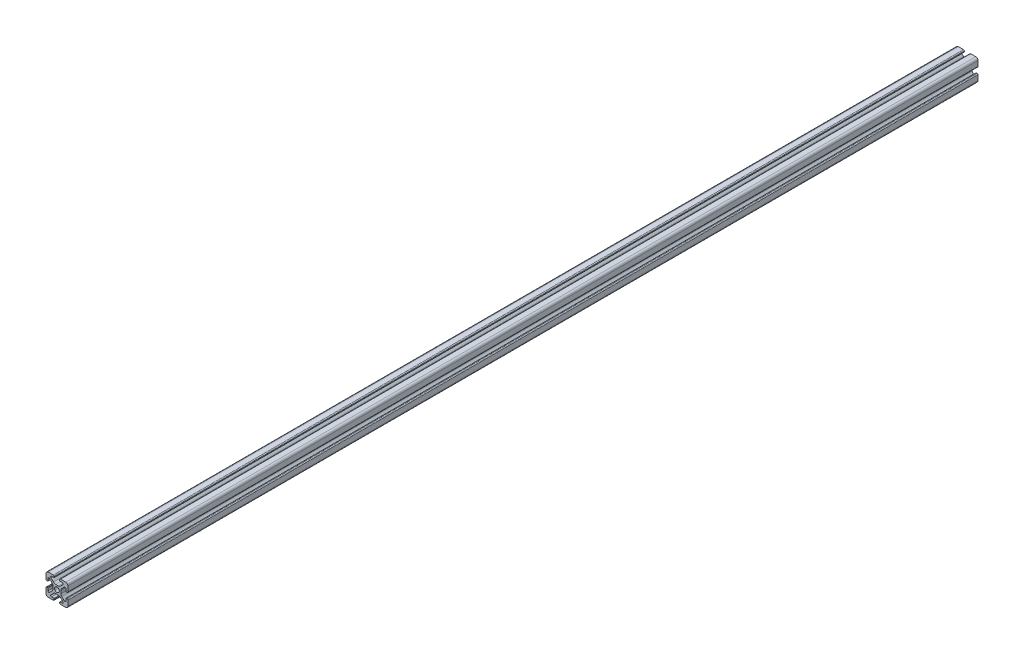
SolidWorks part; units mm, degrees
ref_plane "Plan de face" through (0, 0, 0) normal (0, 0, 1) x (1, 0, 0)
ref_plane "Plan de dessus" through (0, 0, 0) normal (0, 1, 0) x (1, 0, 0)
ref_plane "Plan de droite" through (0, 0, 0) normal (1, 0, 0) x (0, 0, -1)
ref_plane "Plan1" through (0, 0, 0) normal (0, 0, -1) x (-1, 0, 0)
sketch "Esquisse1" plane through (0, 0, 0) normal (0, 0, -1) x (-1, 0, 0)
  line L0 (-20, 6.7) -> (-20, 2)
  line L1 (-18, 0) -> (-13.3, 0)
  line L2 (-12.5, 0.8) -> (-12.5, 1.5)
  line L3 (-12.8, 1.8) -> (-14.9184, 1.8)
  line L4 (-15.5064, 3.2196) -> (-13.2547, 5.4713)
  line L5 (-11.1334, 6.35) -> (-8.8666, 6.35)
  line L6 (-6.7453, 5.4713) -> (-4.4936, 3.2196)
  line L7 (-5.0816, 1.8) -> (-7.2, 1.8)
  line L8 (-7.5, 1.5) -> (-7.5, 0.8)
  line L9 (-6.7, 0) -> (-2, 0)
  line L10 (0, 2) -> (0, 6.7)
  line L11 (-0.8, 7.5) -> (-1.5, 7.5)
  line L12 (-1.8, 7.2) -> (-1.8, 5.0816)
  line L13 (-3.2196, 4.4936) -> (-5.4713, 6.7453)
  line L14 (-6.35, 8.8666) -> (-6.35, 11.1334)
  line L15 (-5.4713, 13.2547) -> (-3.2196, 15.5064)
  line L16 (-1.8, 14.9184) -> (-1.8, 12.8)
  line L17 (-1.5, 12.5) -> (-0.8, 12.5)
  line L18 (0, 13.3) -> (0, 18)
  line L19 (-2, 20) -> (-6.7, 20)
  line L20 (-7.5, 19.2) -> (-7.5, 18.5)
  line L21 (-7.2, 18.2) -> (-5.0816, 18.2)
  line L22 (-4.4936, 16.7804) -> (-6.7453, 14.5287)
  line L23 (-8.8666, 13.65) -> (-11.1334, 13.65)
  line L24 (-13.2547, 14.5287) -> (-15.5064, 16.7804)
  line L25 (-14.9184, 18.2) -> (-12.8, 18.2)
  line L26 (-12.5, 18.5) -> (-12.5, 19.2)
  line L27 (-13.3, 20) -> (-18, 20)
  line L28 (-20, 18) -> (-20, 13.3)
  line L29 (-19.2, 12.5) -> (-18.5, 12.5)
  line L30 (-18.2, 12.8) -> (-18.2, 14.9184)
  line L31 (-16.7804, 15.5064) -> (-14.5287, 13.2547)
  line L32 (-13.65, 11.1334) -> (-13.65, 8.8666)
  line L33 (-14.5287, 6.7453) -> (-16.7804, 4.4936)
  line L34 (-18.2, 5.0816) -> (-18.2, 7.2)
  line L35 (-18.5, 7.5) -> (-19.2, 7.5)
  arc A0 (-19.2, 7.5) -> (-20, 6.7) centre (-19.2, 6.7) ccw
  arc A1 (-20, 2) -> (-18, 0) centre (-18, 2) ccw
  arc A2 (-13.3, 0) -> (-12.5, 0.8) centre (-13.3, 0.8) ccw
  arc A3 (-12.5, 1.5) -> (-12.8, 1.8) centre (-12.8, 1.5) ccw
  arc A4 (-14.9184, 1.8) -> (-15.5064, 3.2196) centre (-14.9184, 2.6316) cw
  arc A5 (-13.2547, 5.4713) -> (-11.1334, 6.35) centre (-11.1334, 3.35) cw
  arc A6 (-8.8666, 6.35) -> (-6.7453, 5.4713) centre (-8.8666, 3.35) cw
  arc A7 (-4.4936, 3.2196) -> (-5.0816, 1.8) centre (-5.0816, 2.6316) cw
  arc A8 (-7.2, 1.8) -> (-7.5, 1.5) centre (-7.2, 1.5) ccw
  arc A9 (-7.5, 0.8) -> (-6.7, 0) centre (-6.7, 0.8) ccw
  arc A10 (-2, 0) -> (0, 2) centre (-2, 2) ccw
  arc A11 (0, 6.7) -> (-0.8, 7.5) centre (-0.8, 6.7) ccw
  arc A12 (-1.5, 7.5) -> (-1.8, 7.2) centre (-1.5, 7.2) ccw
  arc A13 (-1.8, 5.0816) -> (-3.2196, 4.4936) centre (-2.6316, 5.0816) cw
  arc A14 (-5.4713, 6.7453) -> (-6.35, 8.8666) centre (-3.35, 8.8666) cw
  arc A15 (-6.35, 11.1334) -> (-5.4713, 13.2547) centre (-3.35, 11.1334) cw
  arc A16 (-3.2196, 15.5064) -> (-1.8, 14.9184) centre (-2.6316, 14.9184) cw
  arc A17 (-1.8, 12.8) -> (-1.5, 12.5) centre (-1.5, 12.8) ccw
  arc A18 (-0.8, 12.5) -> (0, 13.3) centre (-0.8, 13.3) ccw
  arc A19 (0, 18) -> (-2, 20) centre (-2, 18) ccw
  arc A20 (-6.7, 20) -> (-7.5, 19.2) centre (-6.7, 19.2) ccw
  arc A21 (-7.5, 18.5) -> (-7.2, 18.2) centre (-7.2, 18.5) ccw
  arc A22 (-5.0816, 18.2) -> (-4.4936, 16.7804) centre (-5.0816, 17.3684) cw
  arc A23 (-6.7453, 14.5287) -> (-8.8666, 13.65) centre (-8.8666, 16.65) cw
  arc A24 (-11.1334, 13.65) -> (-13.2547, 14.5287) centre (-11.1334, 16.65) cw
  arc A25 (-15.5064, 16.7804) -> (-14.9184, 18.2) centre (-14.9184, 17.3684) cw
  arc A26 (-12.8, 18.2) -> (-12.5, 18.5) centre (-12.8, 18.5) ccw
  arc A27 (-12.5, 19.2) -> (-13.3, 20) centre (-13.3, 19.2) ccw
  arc A28 (-18, 20) -> (-20, 18) centre (-18, 18) ccw
  arc A29 (-20, 13.3) -> (-19.2, 12.5) centre (-19.2, 13.3) ccw
  arc A30 (-18.5, 12.5) -> (-18.2, 12.8) centre (-18.5, 12.8) ccw
  arc A31 (-18.2, 14.9184) -> (-16.7804, 15.5064) centre (-17.3684, 14.9184) cw
  arc A32 (-14.5287, 13.2547) -> (-13.65, 11.1334) centre (-16.65, 11.1334) cw
  arc A33 (-13.65, 8.8666) -> (-14.5287, 6.7453) centre (-16.65, 8.8666) cw
  arc A34 (-16.7804, 4.4936) -> (-18.2, 5.0816) centre (-17.3684, 5.0816) cw
  arc A35 (-18.2, 7.2) -> (-18.5, 7.5) centre (-18.5, 7.2) ccw
  circle A36 centre (-10, 10) radius 2.15
extrude "Boss.-Extru.1" add sketch "Esquisse1" against normal blind 832
